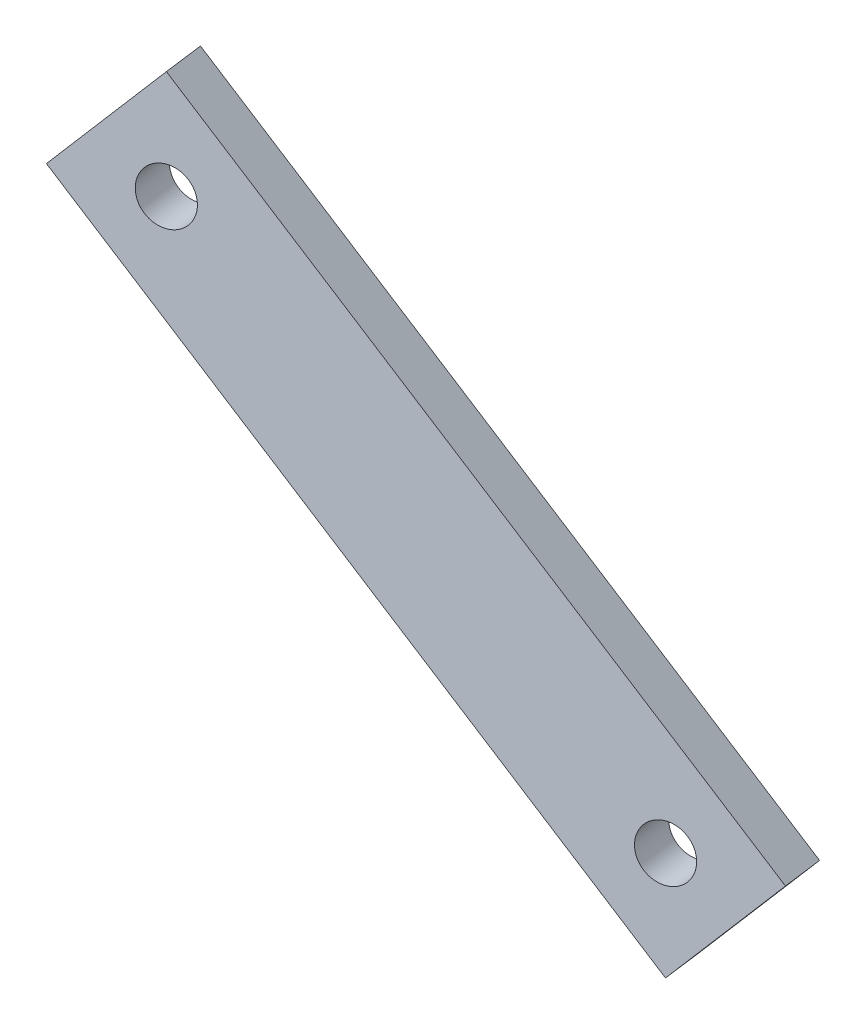
SolidWorks part; units mm, degrees
ref_plane "Płaszczyzna przednia" through (0, 0, 0) normal (0, 0, 1) x (1, 0, 0)
ref_plane "Płaszczyzna górna" through (0, 0, 0) normal (0, 1, 0) x (1, 0, 0)
ref_plane "Płaszczyzna prawa" through (0, 0, 0) normal (1, 0, 0) x (0, 0, -1)
sketch "Szkic3" plane through (38.1606, 20.2078, 157.3093) normal (0.2339, 0.1239, 0.9643) x (0.9723, -0.0298, -0.232)
  line L0 (-69.6663, -102.5536) -> (-79.2649, -94.7824) construction
  line L1 (-75.4894, -90.1192) -> (-65.8909, -97.8903) construction
  line L2 (-69.6663, -102.5536) -> (-79.2649, -94.7824)
  line L3 (-75.4894, -90.1192) -> (-65.8909, -97.8903)
  line L4 (-65.8909, -97.8903) -> (-52.9501, -108.3673)
  line L5 (-52.9501, -108.3673) -> (-56.7256, -113.0306)
  line L6 (-56.7256, -113.0306) -> (-69.6663, -102.5536)
  line L7 (-80.8192, -93.524) -> (-77.0437, -88.8608)
  line L8 (-77.0437, -88.8608) -> (-75.4894, -90.1192)
  line L9 (-80.8192, -93.524) -> (-79.2649, -94.7824)
  circle A2 centre (-57.1693, -108.811) radius 1.1 construction
  circle A3 centre (-76.5997, -93.08) radius 1.1 construction
  circle A6 centre (-57.1693, -108.811) radius 1.1
  circle A7 centre (-76.5997, -93.08) radius 1.1
  dimension "D1" = 6
  dimension "D2" = 6
  dimension "D3" = 3
  dimension "D4" = 3
extrude "Dodanie-wyciągnięcie2" add sketch "Szkic3" along normal blind 2
